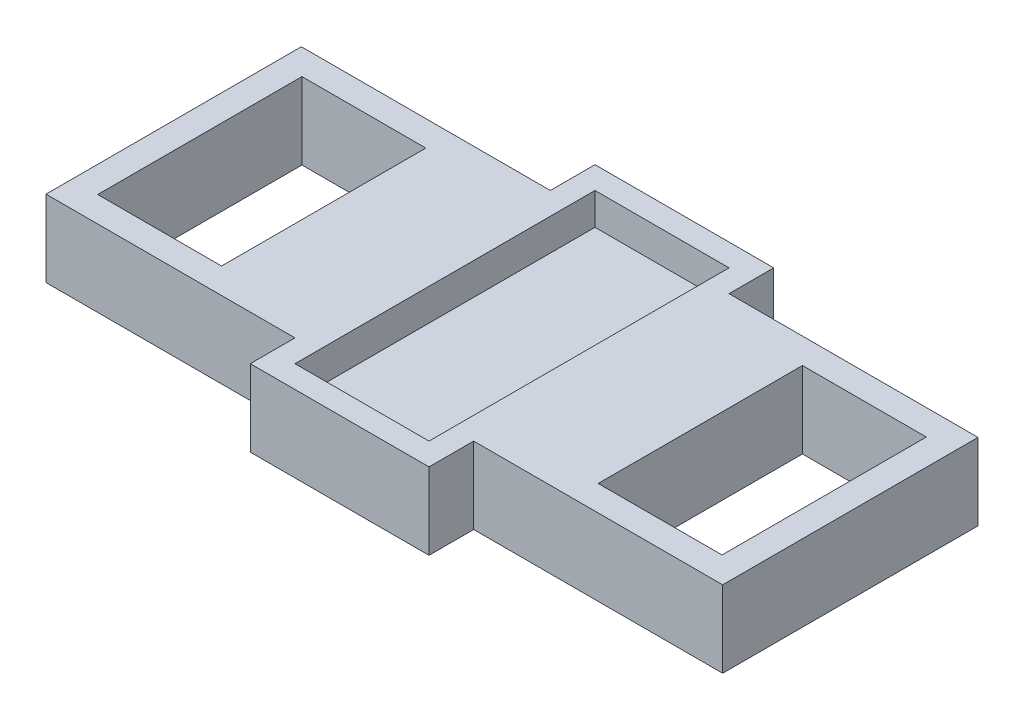
SolidWorks part; units mm, degrees
ref_plane "Płaszczyzna przednia" through (0, 0, 0) normal (0, 0, 1) x (1, 0, 0)
ref_plane "Płaszczyzna górna" through (0, 0, 0) normal (0, 1, 0) x (1, 0, 0)
ref_plane "Płaszczyzna prawa" through (0, 0, 0) normal (1, 0, 0) x (0, 0, -1)
sketch "Szkic1" plane through (0, 0, 0) normal (0, 1, 0) x (1, 0, 0)
  line L0 (-7, 10) -> (-7, 13.5)
  line L1 (26.5, -10) -> (7, -10)
  line L2 (26.5, -10) -> (26.5, 10)
  line L3 (26.5, 10) -> (7, 10)
  line L4 (-26.5, -10) -> (-26.5, 10)
  line L5 (26.5, -10) -> (-26.5, 10) construction
  line L6 (26.5, 10) -> (-26.5, -10) construction
  line L7 (7, -13.5) -> (-7, -13.5)
  line L8 (7, -13.5) -> (7, -10)
  line L9 (7, 13.5) -> (-7, 13.5)
  line L10 (-7, -13.5) -> (-7, -10)
  line L11 (7, -13.5) -> (-7, 13.5) construction
  line L12 (7, 13.5) -> (-7, -13.5) construction
  line L13 (-7, 10) -> (-26.5, 10)
  line L14 (7, 10) -> (7, 13.5)
  line L15 (-7, -10) -> (-26.5, -10)
  point P0 (0, 0)
  point P6 (0, 0)
  dimension "D1" = 20
  dimension "D2" = 53
  dimension "D3" = 14
  dimension "D4" = 27
extrude "Dodanie-wyciągnięcie1" add sketch "Szkic1" along normal blind 6
sketch "Szkic2" plane through (0, 6, 0) normal (0, 1, 0) x (1, 0, 0)
  line L0 (0, 10) -> (0, -10) construction
  line L1 (-24.45, 8) -> (-14.75, 8)
  line L2 (-24.45, 8) -> (-24.45, -8)
  line L3 (-24.45, -8) -> (-14.75, -8)
  line L4 (-14.75, 8) -> (-14.75, -8)
  line L5 (-24.45, 8) -> (-14.75, -8) construction
  line L6 (-24.45, -8) -> (-14.75, 8) construction
  line L9 (24.45, -8) -> (14.75, -8)
  line L10 (14.75, 8) -> (14.75, -8)
  line L11 (24.45, 8) -> (14.75, 8)
  line L12 (24.45, 8) -> (24.45, -8)
  point P0 (-19.6, 0)
  dimension "D1" = 16
  dimension "D2" = 9.7
  dimension "D3" = 29.5
extrude "Wytnij-wyciągnięcie1" cut sketch "Szkic2" against normal up to next contours L1 L4 L3 L2 | L11 L10 L9 L12
sketch "Szkic4" plane through (0, 6, 0) normal (0, -1, 0) x (1, 0, 0)
  line L1 (5.25, -11.75) -> (-5.25, -11.75)
  line L2 (5.25, -11.75) -> (5.25, 11.75)
  line L3 (5.25, 11.75) -> (-5.25, 11.75)
  line L4 (-5.25, -11.75) -> (-5.25, 11.75)
  line L5 (5.25, -11.75) -> (-5.25, 11.75) construction
  line L6 (5.25, 11.75) -> (-5.25, -11.75) construction
  point P0 (0, 0)
  dimension "D1" = 10.5
  dimension "D2" = 23.5
extrude "Wytnij-wyciągnięcie3" cut sketch "Szkic4" along normal blind 2.5
